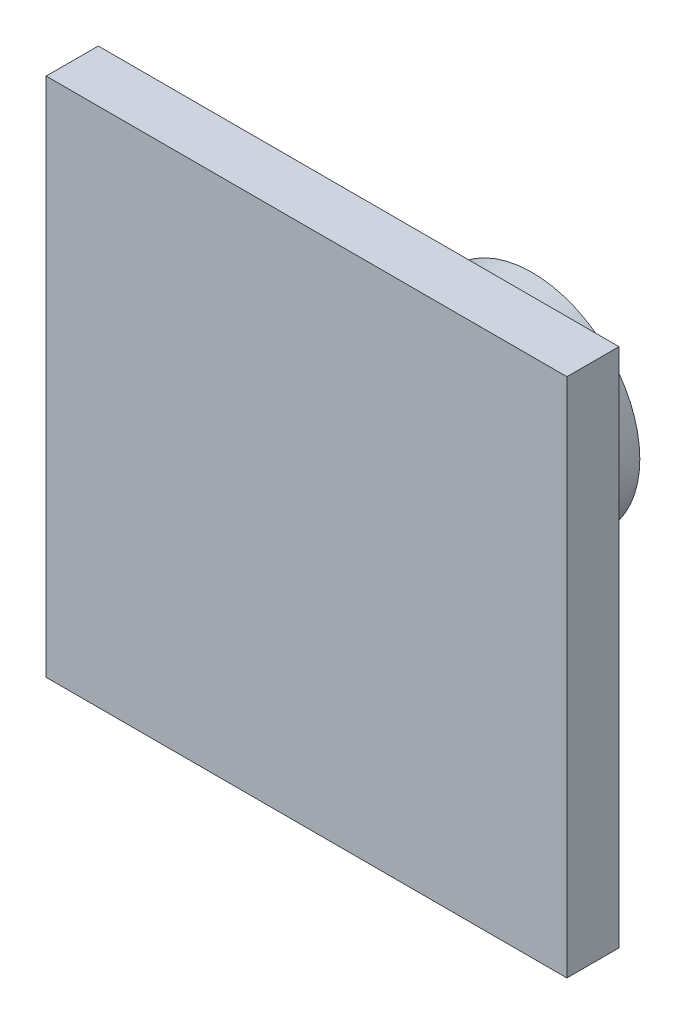
SolidWorks part; units mm, degrees
material "Сосна"
ref_plane "Front" through (0, 0, 0) normal (0, 0, 1) x (1, 0, 0)
ref_plane "Top" through (0, 0, 0) normal (0, 1, 0) x (1, 0, 0)
ref_plane "Right" through (0, 0, 0) normal (1, 0, 0) x (0, 0, -1)
sketch "Эскиз2" plane through (0, 0, 0) normal (0, 0, 1) x (1, 0, 0)
  line L1 (-7.5, -7.5) -> (7.5, -7.5)
  line L2 (-7.5, -7.5) -> (-7.5, 7.5)
  line L3 (-7.5, 7.5) -> (7.5, 7.5)
  line L4 (7.5, -7.5) -> (7.5, 7.5)
  line L5 (-7.5, -7.5) -> (7.5, 7.5) construction
  line L6 (-7.5, 7.5) -> (7.5, -7.5) construction
  point P0 (0, 0)
  dimension "D1" = 15
extrude "Основание" add sketch "Эскиз2" along normal blind 1.5
sketch "Эскиз3" plane through (0, 0, 0) normal (0, 0, 1) x (1, 0, 0)
  circle A0 centre (0, 0) radius 1.1
  circle A1 centre (0, 0) radius 3.1
  dimension "D1" = 2.2
  dimension "D2" = 2
  dimension "D3" = 6.2
extrude "Стойка" add sketch "Эскиз3" against normal blind 5
chamfer "Фаска1" distance 2 angle 45 1 edges at (3.1, 0, 0)
